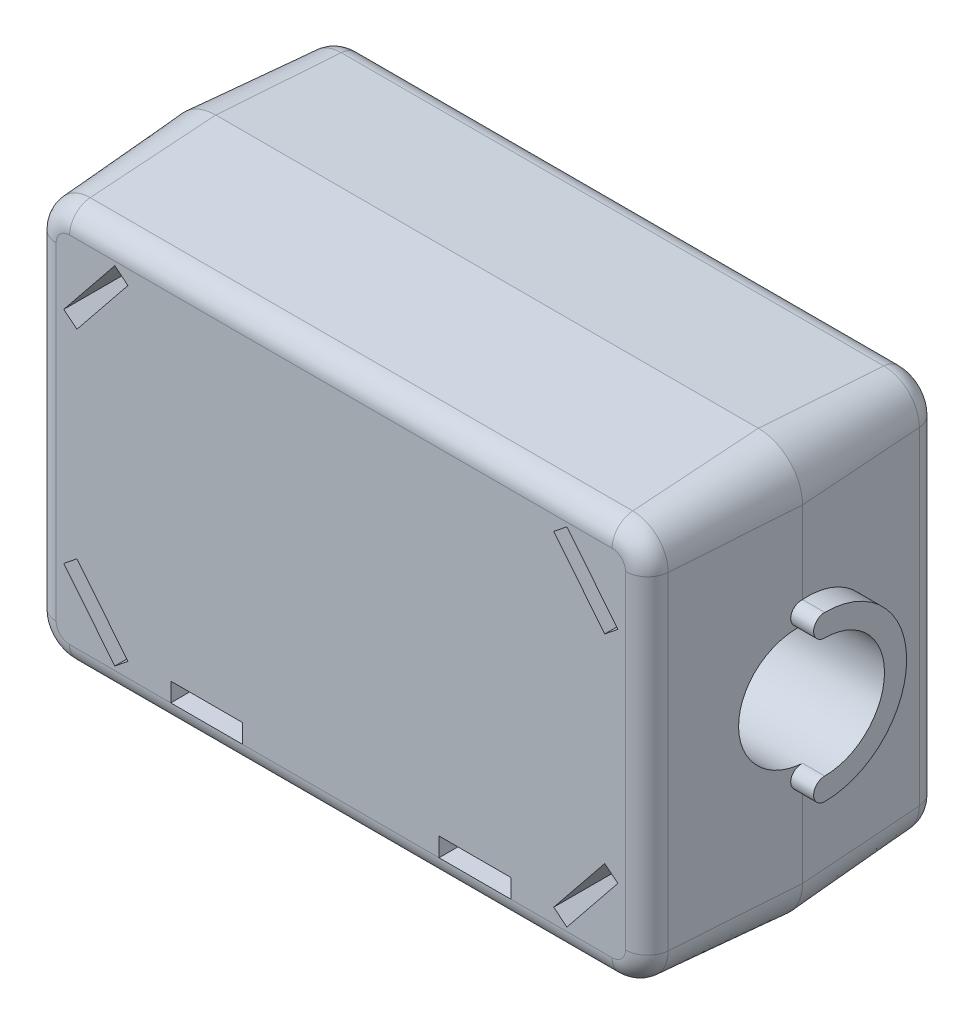
SolidWorks part; units mm, degrees
ref_plane "Face" through (0, 0, 0) normal (0, 0, 1) x (1, 0, 0)
ref_plane "Dessus" through (0, 0, 0) normal (0, 1, 0) x (1, 0, 0)
ref_plane "Droite" through (0, 0, 0) normal (1, 0, 0) x (0, 0, -1)
sketch "Esquisse1" plane through (0, 0, 0) normal (0, 0, 1) x (1, 0, 0)
  line L1 (2, 0) -> (26.5, 0)
  line L2 (0, 2) -> (0, 16.8)
  line L3 (2, 18.8) -> (26.5, 18.8)
  line L4 (28.5, 2) -> (28.5, 16.8)
  arc A0 (0, 16.8) -> (2, 18.8) centre (2, 16.8) cw
  arc A1 (26.5, 18.8) -> (28.5, 16.8) centre (26.5, 16.8) cw
  arc A2 (26.5, 0) -> (28.5, 2) centre (26.5, 2) ccw
  arc A3 (2, 0) -> (0, 2) centre (2, 2) cw
  point P6 (0, 18.8)
  point P9 (28.5, 18.8)
  point P12 (28.5, 0)
  point P15 (0, 0)
  dimension "D3" = 2
  dimension "D1" = 28.5
  dimension "D2" = 18.8
extrude "Extrusion1" add sketch "Esquisse1" along normal mid plane 13.2 draft 4
fillet "Congé1" radius 1 16 edges at (0.9121, 0.9121, 6.6) (14.25, 0.4615, 6.6) (27.5879, 0.9121, 6.6) (28.0385, 9.4, 6.6) (27.5879, 17.8879, 6.6) (14.25, 18.3385, 6.6) (0.9121, 17.8879, -6.6) (14.25, 18.3385, -6.6) (27.5879, 17.8879, -6.6) (28.0385, 9.4, -6.6) (27.5879, 0.9121, -6.6) (14.25, 0.4615, -6.6) (0.9121, 0.9121, -6.6) (0.4615, 9.4, -6.6) (0.9121, 17.8879, 6.6) (0.4615, 9.4, 6.6)
sketch "Esquisse2" plane through (0, 0, 0) normal (1, 0, 0) x (0, 0, -1)
  line L0 (0, 2) -> (0, 16.8) construction
  circle A0 centre (0, 9.4) radius 2.7
extrude "Enlèv. mat.-Extru.1" cut sketch "Esquisse2" along normal through all
ref_plane "Plan1" through (10, 0, 0) normal (1, 0, 0) x (0, 0, -1)
sketch "Esquisse3" plane through (10, 0, 0) normal (1, 0, 0) x (0, 0, -1)
  arc A0 (0, 12.1) -> (0, 6.7) centre (0, 9.4) ccw construction
  arc A1 (0, 12.1) -> (0, 6.7) centre (0, 9.4) ccw
  arc A2 (0, 13.1) -> (0, 5.7) centre (0, 9.4) ccw
  arc A3 (0, 5.7) -> (0, 6.7) centre (0, 6.2) ccw
  arc A4 (0, 13.1) -> (0, 12.1) centre (0, 12.6) cw
  dimension "D1" = 1
extrude "Extrusion2" add sketch "Esquisse3" against normal blind 11
sketch "Esquisse4" plane through (10, 0, 0) normal (1, 0, 0) x (0, 0, -1)
  arc A0 (0, 6.7) -> (0, 12.1) centre (0, 9.4) ccw construction
  arc A1 (0, 6.7) -> (0, 12.1) centre (0, 9.4) ccw
  arc A2 (0, 5.7) -> (0, 13.1) centre (0, 9.4) ccw
  arc A3 (0, 6.7) -> (0, 5.7) centre (0, 6.2) ccw
  arc A4 (0, 13.1) -> (0, 12.1) centre (0, 12.6) ccw
  dimension "D1" = 1
extrude "Extrusion3" add sketch "Esquisse4" along normal blind 19.5
sketch "Esquisse5" plane through (0, 0, 6.6) normal (0, 0, 1) x (1, 0, 0)
  line L0 (14.25, 1.394) -> (14.25, 13.1563) construction
  line L1 (2, 1.394) -> (26.5, 1.394) construction
  line L2 (18.6831, 1.394) -> (18.6831, 2.2463)
  line L3 (6.5695, 1.394) -> (9.8169, 1.394)
  line L4 (6.5695, 1.394) -> (6.5695, 2.2463)
  line L5 (6.5695, 2.2463) -> (9.8169, 2.2463)
  line L6 (9.8169, 1.394) -> (9.8169, 2.2463)
  line L7 (21.9305, 2.2463) -> (18.6831, 2.2463)
  line L8 (21.9305, 1.394) -> (21.9305, 2.2463)
  line L9 (21.9305, 1.394) -> (18.6831, 1.394)
  line L10 (1.738, 14.3675) -> (4.0415, 17.2271)
  line L11 (1.394, 9.4) -> (13.0969, 9.4) construction
  line L12 (1.394, 16.8) -> (1.394, 2) construction
  line L13 (2.3328, 4.9116) -> (4.6363, 2.0521)
  line L14 (4.0415, 1.5729) -> (4.6363, 2.0521)
  line L15 (1.738, 14.3675) -> (2.3328, 13.8884)
  line L16 (4.0415, 17.2271) -> (4.6363, 16.7479)
  line L17 (2.3328, 13.8884) -> (4.6363, 16.7479)
  line L18 (1.738, 4.4325) -> (2.3328, 4.9116)
  line L19 (1.738, 4.4325) -> (4.0415, 1.5729)
  line L20 (26.762, 4.4325) -> (24.4585, 1.5729)
  line L21 (26.762, 4.4325) -> (26.1672, 4.9116)
  line L22 (26.1672, 13.8884) -> (23.8637, 16.7479)
  line L23 (24.4585, 17.2271) -> (23.8637, 16.7479)
  line L24 (26.762, 14.3675) -> (26.1672, 13.8884)
  line L25 (24.4585, 1.5729) -> (23.8637, 2.0521)
  line L26 (26.1672, 4.9116) -> (23.8637, 2.0521)
  line L27 (26.762, 14.3675) -> (24.4585, 17.2271)
extrude "Extrusion4" cut sketch "Esquisse5" against normal blind 5
